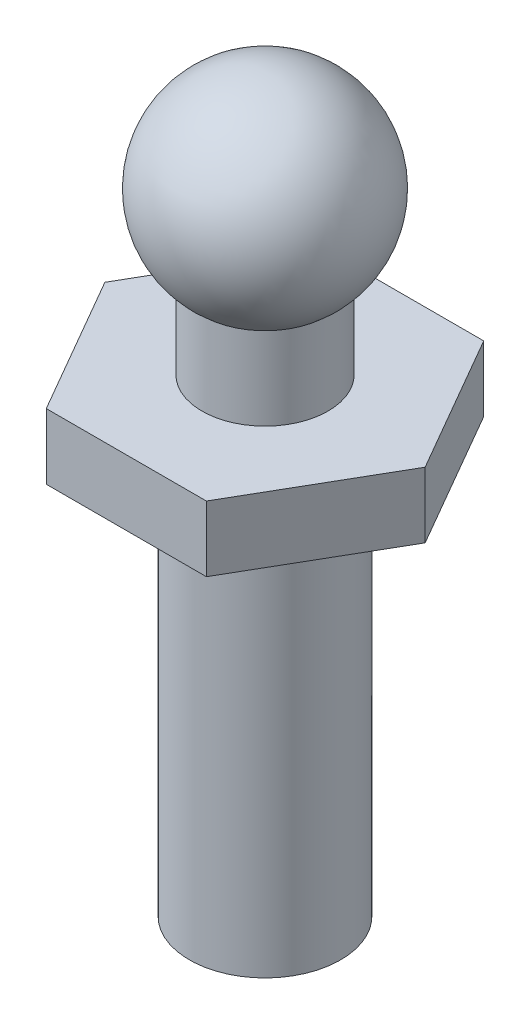
SolidWorks part; units mm, degrees
ref_plane "Plan de face" through (0, 0, 0) normal (0, 0, 1) x (1, 0, 0)
ref_plane "Plan de dessus" through (0, 0, 0) normal (0, 1, 0) x (1, 0, 0)
ref_plane "Plan de droite" through (0, 0, 0) normal (1, 0, 0) x (0, 0, -1)
sketch "Esquisse1" plane through (0, 0, 0) normal (0, 0, 1) x (1, 0, 0)
  line L1 (0, 2) -> (0, -12.5)
  line L2 (0, -12.5) -> (1.5, -12.5)
  line L3 (1.5, -12.5) -> (1.5, -4.5)
  line L4 (1.5, -4.5) -> (2.75, -4.5)
  line L5 (2.75, -4.5) -> (2.75, -3.2)
  line L6 (2.75, -3.2) -> (1.25, -3.2)
  line L7 (1.25, -3.2) -> (1.25, -1.5612)
  line L8 (0, 0) -> (0, 14.5) construction
  arc A0 (1.25, -1.5612) -> (0, 2) centre (0, 0) ccw
  dimension "D1" = 2
  dimension "D2" = 3
  dimension "D3" = 8
  dimension "D4" = 1.3
  dimension "D6" = 2.5
  dimension "D7" = 4.5
  dimension "D8" = 5.5
revolve "Révolution1" add sketch "Esquisse1" angle 360 about L8
sketch "Esquisse2" plane through (0, -3.2, 0) normal (0, 1, 0) x (1, 0, 0)
  line L1 (1.5877, 2.75) -> (-1.5877, 2.75)
  line L2 (-1.5877, 2.75) -> (-3.1754, 0)
  line L3 (-3.1754, 0) -> (-1.5877, -2.75)
  line L4 (-1.5877, -2.75) -> (1.5877, -2.75)
  line L5 (1.5877, -2.75) -> (3.1754, 0)
  line L6 (3.1754, 0) -> (1.5877, 2.75)
  circle A0 centre (0, 0) radius 2.75 construction
  circle A1 centre (0, 0) radius 2.75 construction
extrude "Boss.-Extru.1" add sketch "Esquisse2" against normal up to surface (1.3 mm away) up to face at (0, -4.5, -2.75)
